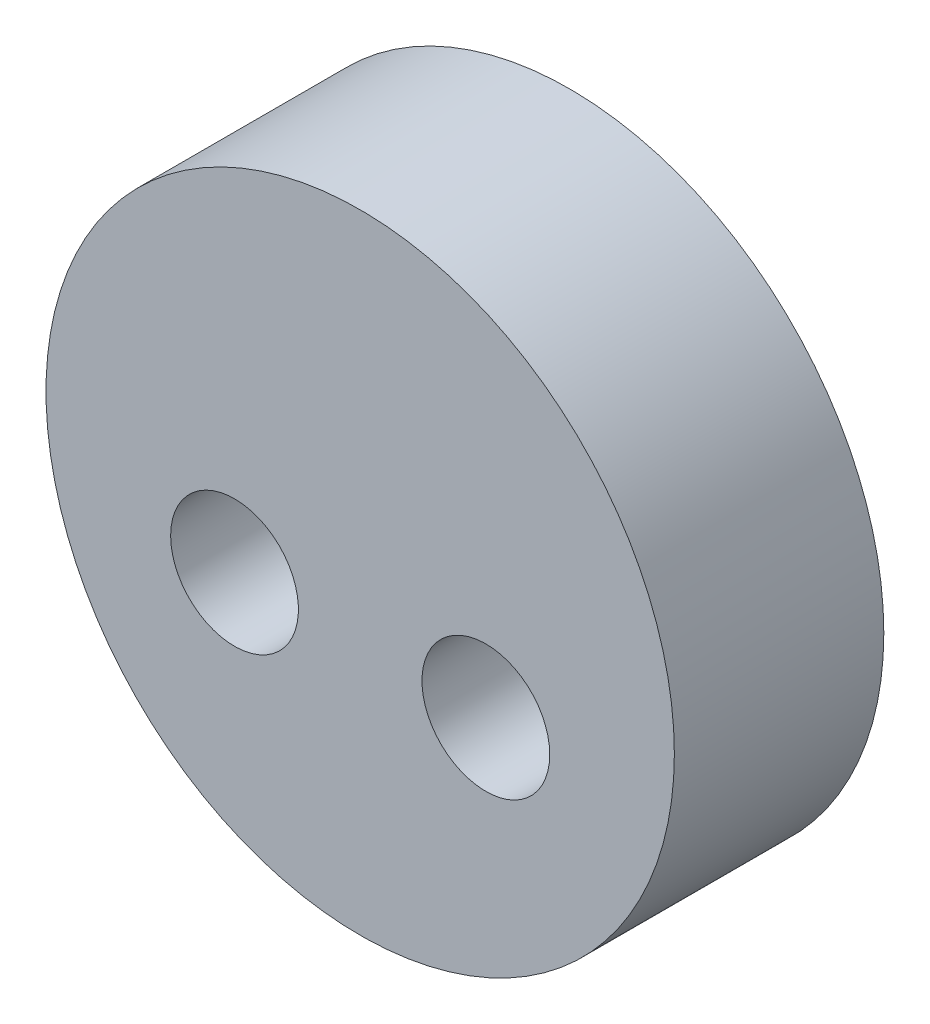
SolidWorks part; units mm, degrees
ref_plane "Front Plane" through (0, 0, 0) normal (0, 0, 1) x (1, 0, 0)
ref_plane "Top Plane" through (0, 0, 0) normal (0, 1, 0) x (1, 0, 0)
ref_plane "Right Plane" through (0, 0, 0) normal (1, 0, 0) x (0, 0, -1)
sketch "Sketch1" plane through (0, 0, 0) normal (0, 0, 1) x (1, 0, 0)
  circle A0 centre (0, 0) radius 7.5
  dimension "D1" = 15
extrude "Boss-Extrude1" add sketch "Sketch1" along normal blind 5
sketch "Sketch2" plane through (0, 0, 5) normal (0, 0, 1) x (1, 0, 0)
  line L0 (-8.6616, 0) -> (8.2232, 0) construction
  line L1 (-8.6616, -1.5) -> (8.2232, -1.5) construction
  line L2 (0, 7.8726) -> (0, -8.083) construction
  circle A0 centre (3, -1.5) radius 1.525
  circle A1 centre (-3, -1.5) radius 1.525
  dimension "D2" = 3.05
  dimension "D1" = 1.5
  dimension "D3" = 3
extrude "Cut-Extrude1" cut sketch "Sketch2" against normal through all
